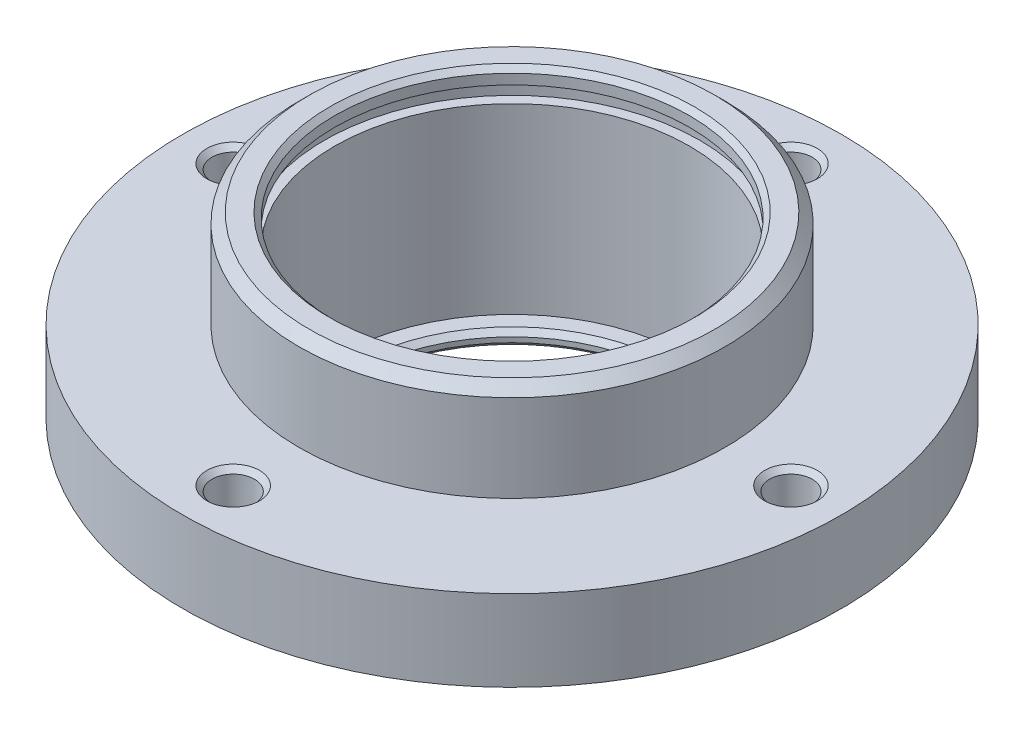
SolidWorks part; units mm, degrees
material "Д16Т ГОСТ 4784-74"
ref_plane "Спереди" through (0, 0, 0) normal (0, 0, 1) x (1, 0, 0)
ref_plane "Сверху" through (0, 0, 0) normal (0, 1, 0) x (1, 0, 0)
ref_plane "Справа" through (0, 0, 0) normal (1, 0, 0) x (0, 0, -1)
sketch "Эскиз1" plane through (0, 0, 0) normal (0, 0, 1) x (1, 0, 0)
  line L0 (-22.5, 5) -> (-22.5, 2)
  line L1 (-22.5, 5) -> (-32.5, 5)
  line L2 (-17.5, 1.5) -> (-15.5, 1.5)
  line L3 (-15.5, 1.5) -> (-15.5, 0)
  line L4 (-32.5, 5) -> (-32.5, 13)
  line L5 (-20, 22.6) -> (-17.5, 22.6)
  line L6 (-21, 21.6) -> (-21, 13)
  line L7 (-20.5, 0) -> (-15.5, 0)
  line L8 (-17.5, 21.1) -> (-17.5, 22.6)
  line L9 (-17.5, 19.5) -> (-18.5, 19.5)
  line L10 (0, 0) -> (0, 22.6) construction
  line L11 (-21, 21.6) -> (-20, 22.6)
  line L12 (-17.5, 1.5) -> (-17.5, 19.5)
  line L13 (-21, 13) -> (-32.5, 13)
  line L14 (-17.5, 21.1) -> (-18.5, 21.1)
  line L15 (-18.5, 19.5) -> (-18.5, 21.1)
  line L16 (-22.5, 2) -> (-20.5, 0)
  point P4 (-21, 22.6)
  point P7 (-22.5, 0)
  dimension "D1" = 22.6
  dimension "D2" = 35
  dimension "D3" = 1.5
  dimension "D4" = 2
  dimension "D5" = 8
  dimension "D6" = 5
  dimension "D7" = 37
  dimension "D8" = 65
  dimension "D9" = 45
  dimension "D10" = 1.5
  dimension "D11" = 1.6
  dimension "D12" = 42
  dimension "D13" = 18
revolve "Повернуть1" add sketch "Эскиз1" angle 360 about L10
sketch "Эскиз2" plane through (0, 5, 0) normal (0, -1, 0) x (1, 0, 0)
  line L0 (0, 0) -> (0, 27.5) construction
  circle A0 centre (0, 0) radius 27.5 construction
  circle A1 centre (0, 27.5) radius 2.1
  circle A2 centre (27.5, 0) radius 2.1
  circle A3 centre (0, -27.5) radius 2.1
  circle A4 centre (-27.5, 0) radius 2.1
  dimension "D1" = 4
  dimension "D2" = 4.2
  dimension "D3" = 55
extrude "Вырез-Вытянуть1" cut sketch "Эскиз2" against normal through all
cosmetic thread "Условное изображение резьбы1" parameters "D2"=5
cosmetic thread "Условное изображение резьбы2" parameters "D2"=5
cosmetic thread "Условное изображение резьбы3" parameters "D2"=5
cosmetic thread "Условное изображение резьбы4" parameters "D2"=5
chamfer "Фаска1" distance 0.5 angle 45 3 edges at (0, 0, -15.5) (0, 1.5, -15.5) (0, 22.6, -17.5)
chamfer "Фаска2" distance 0.5 angle 45 8 edges at (-27.5, 13, -2.1) (-25.4, 5, 0) (0, 13, -29.6) (2.1, 5, -27.5) (0, 13, 25.4) (2.1, 5, 27.5) (27.5, 13, -2.1) (29.6, 5, 0)
